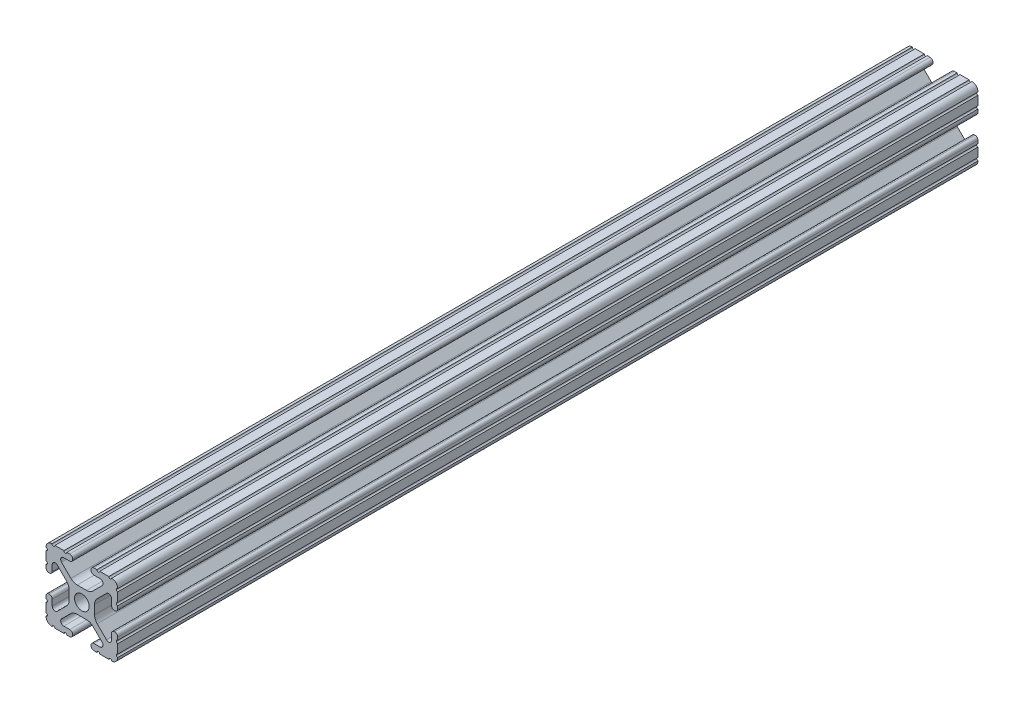
SolidWorks part; units mm, degrees
ref_plane "Front Plane" through (0, 0, 0) normal (0, 0, 1) x (1, 0, 0)
ref_plane "Top Plane" through (0, 0, 0) normal (0, 1, 0) x (1, 0, 0)
ref_plane "Right Plane" through (0, 0, 0) normal (1, 0, 0) x (0, 0, -1)
sketch "Sketch1" plane through (0, 0, 0) normal (0, 0, 1) x (1, 0, 0)
  line L88 (-7.1797, -8.6452) -> (-3.9523, -5.4237)
  line L89 (-1.7093, -4.4958) -> (1.7093, -4.4958)
  line L90 (3.9523, -5.4237) -> (7.1797, -8.6452)
  line L91 (6.4164, -10.4902) -> (4.2875, -10.4902)
  line L92 (3.2385, -11.5392) -> (3.2385, -11.651)
  line L93 (4.2875, -12.7) -> (5.3171, -12.7)
  line L94 (6.3331, -12.7) -> (9.5504, -12.7)
  line L95 (12.7, -9.5504) -> (12.7, -6.3331)
  line L96 (12.7, -5.3171) -> (12.7, -4.2875)
  line L97 (11.651, -3.2385) -> (11.5392, -3.2385)
  line L98 (10.4902, -4.2875) -> (10.4902, -6.4021)
  line L99 (8.7371, -7.1294) -> (5.441, -3.8408)
  line L100 (4.5085, -1.5932) -> (4.5085, 1.5932)
  line L101 (5.441, 3.8408) -> (8.7371, 7.1294)
  line L102 (10.4902, 6.4021) -> (10.4902, 4.2875)
  line L103 (11.5392, 3.2385) -> (11.651, 3.2385)
  line L104 (12.7, 4.2875) -> (12.7, 5.3171)
  line L105 (12.7, 6.3331) -> (12.7, 9.5504)
  line L106 (9.5504, 12.7) -> (6.3331, 12.7)
  line L107 (5.3171, 12.7) -> (4.2875, 12.7)
  line L108 (3.2385, 11.651) -> (3.2385, 11.5392)
  line L109 (4.2875, 10.4902) -> (6.4768, 10.4902)
  line L110 (7.207, 8.7244) -> (3.8983, 5.4232)
  line L111 (1.6558, 4.4958) -> (-1.6558, 4.4958)
  line L112 (-3.8983, 5.4232) -> (-7.207, 8.7244)
  line L113 (-6.4768, 10.4902) -> (-4.2875, 10.4902)
  line L114 (-3.2385, 11.5392) -> (-3.2385, 11.651)
  line L115 (-4.2875, 12.7) -> (-5.3171, 12.7)
  line L116 (-6.3331, 12.7) -> (-9.5504, 12.7)
  line L117 (-12.7, 9.5504) -> (-12.7, 6.3331)
  line L118 (-12.7, 5.3171) -> (-12.7, 4.2875)
  line L119 (-11.651, 3.2385) -> (-11.5392, 3.2385)
  line L120 (-10.4902, 4.2875) -> (-10.4902, 6.4021)
  line L121 (-8.7371, 7.1294) -> (-5.441, 3.8408)
  line L122 (-4.5085, 1.5932) -> (-4.5085, -1.5932)
  line L123 (-5.441, -3.8408) -> (-8.7371, -7.1294)
  line L124 (-10.4902, -6.4021) -> (-10.4902, -4.2875)
  line L125 (-11.5392, -3.2385) -> (-11.651, -3.2385)
  line L126 (-12.7, -4.2875) -> (-12.7, -5.3171)
  line L127 (-12.7, -6.3331) -> (-12.7, -9.5504)
  line L128 (-9.5504, -12.7) -> (-6.3331, -12.7)
  line L129 (-5.3171, -12.7) -> (-4.2875, -12.7)
  line L130 (-3.2385, -11.651) -> (-3.2385, -11.5392)
  line L131 (-4.2875, -10.4902) -> (-6.4164, -10.4902)
  circle A1 centre (0, 0) radius 2.6035
  arc A104 (-7.1797, -8.6452) -> (-6.4164, -10.4902) centre (-6.4164, -9.4098) ccw
  arc A105 (-1.7093, -4.4958) -> (-3.9523, -5.4237) centre (-1.7093, -7.6708) ccw
  arc A106 (3.9523, -5.4237) -> (1.7093, -4.4958) centre (1.7093, -7.6708) ccw
  arc A107 (6.4164, -10.4902) -> (7.1797, -8.6452) centre (6.4164, -9.4098) ccw
  arc A108 (4.2875, -10.4902) -> (3.2385, -11.5392) centre (4.2875, -11.5392) ccw
  arc A109 (3.2385, -11.651) -> (4.2875, -12.7) centre (4.2875, -11.651) ccw
  arc A110 (6.3331, -12.7) -> (5.3171, -12.7) centre (5.8251, -12.7) ccw
  arc A111 (10.5664, -12.6998) -> (9.5504, -12.7) centre (10.0584, -12.7) ccw
  arc A112 (10.5664, -12.6998) -> (12.6998, -10.5664) centre (10.5918, -10.5918) ccw
  arc A113 (12.7, -9.5504) -> (12.6998, -10.5664) centre (12.7, -10.0584) ccw
  arc A114 (12.7, -5.3171) -> (12.7, -6.3331) centre (12.7, -5.8251) ccw
  arc A115 (12.7, -4.2875) -> (11.651, -3.2385) centre (11.651, -4.2875) ccw
  arc A116 (11.5392, -3.2385) -> (10.4902, -4.2875) centre (11.5392, -4.2875) ccw
  arc A117 (8.7371, -7.1294) -> (10.4902, -6.4021) centre (9.4628, -6.4021) ccw
  arc A118 (4.5085, -1.5932) -> (5.441, -3.8408) centre (7.6835, -1.5932) ccw
  arc A119 (5.441, 3.8408) -> (4.5085, 1.5932) centre (7.6835, 1.5932) ccw
  arc A120 (10.4902, 6.4021) -> (8.7371, 7.1294) centre (9.4628, 6.4021) ccw
  arc A121 (10.4902, 4.2875) -> (11.5392, 3.2385) centre (11.5392, 4.2875) ccw
  arc A122 (11.651, 3.2385) -> (12.7, 4.2875) centre (11.651, 4.2875) ccw
  arc A123 (12.7, 6.3331) -> (12.7, 5.3171) centre (12.7, 5.8251) ccw
  arc A124 (12.6998, 10.5664) -> (12.7, 9.5504) centre (12.7, 10.0584) ccw
  arc A125 (12.6998, 10.5664) -> (10.5664, 12.6998) centre (10.5918, 10.5918) ccw
  arc A126 (9.5504, 12.7) -> (10.5664, 12.6998) centre (10.0584, 12.7) ccw
  arc A127 (5.3171, 12.7) -> (6.3331, 12.7) centre (5.8251, 12.7) ccw
  arc A128 (4.2875, 12.7) -> (3.2385, 11.651) centre (4.2875, 11.651) ccw
  arc A129 (3.2385, 11.5392) -> (4.2875, 10.4902) centre (4.2875, 11.5392) ccw
  arc A130 (7.207, 8.7244) -> (6.4768, 10.4902) centre (6.4768, 9.4563) ccw
  arc A131 (1.6558, 4.4958) -> (3.8983, 5.4232) centre (1.6558, 7.6708) ccw
  arc A132 (-3.8983, 5.4232) -> (-1.6558, 4.4958) centre (-1.6558, 7.6708) ccw
  arc A133 (-6.4768, 10.4902) -> (-7.207, 8.7244) centre (-6.4768, 9.4563) ccw
  arc A134 (-4.2875, 10.4902) -> (-3.2385, 11.5392) centre (-4.2875, 11.5392) ccw
  arc A135 (-3.2385, 11.651) -> (-4.2875, 12.7) centre (-4.2875, 11.651) ccw
  arc A136 (-6.3331, 12.7) -> (-5.3171, 12.7) centre (-5.8251, 12.7) ccw
  arc A137 (-10.5664, 12.6998) -> (-9.5504, 12.7) centre (-10.0584, 12.7) ccw
  arc A138 (-10.5664, 12.6998) -> (-12.6998, 10.5664) centre (-10.5918, 10.5918) ccw
  arc A139 (-12.7, 9.5504) -> (-12.6998, 10.5664) centre (-12.7, 10.0584) ccw
  arc A140 (-12.7, 5.3171) -> (-12.7, 6.3331) centre (-12.7, 5.8251) ccw
  arc A141 (-12.7, 4.2875) -> (-11.651, 3.2385) centre (-11.651, 4.2875) ccw
  arc A142 (-11.5392, 3.2385) -> (-10.4902, 4.2875) centre (-11.5392, 4.2875) ccw
  arc A143 (-8.7371, 7.1294) -> (-10.4902, 6.4021) centre (-9.4628, 6.4021) ccw
  arc A144 (-4.5085, 1.5932) -> (-5.441, 3.8408) centre (-7.6835, 1.5932) ccw
  arc A145 (-5.441, -3.8408) -> (-4.5085, -1.5932) centre (-7.6835, -1.5932) ccw
  arc A146 (-10.4902, -6.4021) -> (-8.7371, -7.1294) centre (-9.4628, -6.4021) ccw
  arc A147 (-10.4902, -4.2875) -> (-11.5392, -3.2385) centre (-11.5392, -4.2875) ccw
  arc A148 (-11.651, -3.2385) -> (-12.7, -4.2875) centre (-11.651, -4.2875) ccw
  arc A149 (-12.7, -6.3331) -> (-12.7, -5.3171) centre (-12.7, -5.8251) ccw
  arc A150 (-12.6998, -10.5664) -> (-12.7, -9.5504) centre (-12.7, -10.0584) ccw
  arc A151 (-12.6998, -10.5664) -> (-10.5664, -12.6998) centre (-10.5918, -10.5918) ccw
  arc A152 (-9.5504, -12.7) -> (-10.5664, -12.6998) centre (-10.0584, -12.7) ccw
  arc A153 (-5.3171, -12.7) -> (-6.3331, -12.7) centre (-5.8251, -12.7) ccw
  arc A154 (-4.2875, -12.7) -> (-3.2385, -11.651) centre (-4.2875, -11.651) ccw
  arc A155 (-3.2385, -11.5392) -> (-4.2875, -10.4902) centre (-4.2875, -11.5392) ccw
extrude "Boss-Extrude1" add sketch "Sketch1" along normal mid plane 304.8
sketch "Sketch2" plane through (0, 0, 152.4) normal (0, 0, 1) x (1, 0, 0)
  line L1 (-34.4604, 26.8382) -> (28.9028, 26.8382)
  line L2 (-34.4604, 26.8382) -> (-34.4604, -29.3749)
  line L3 (-34.4604, -29.3749) -> (28.9028, -29.3749)
  line L4 (28.9028, 26.8382) -> (28.9028, -29.3749)
